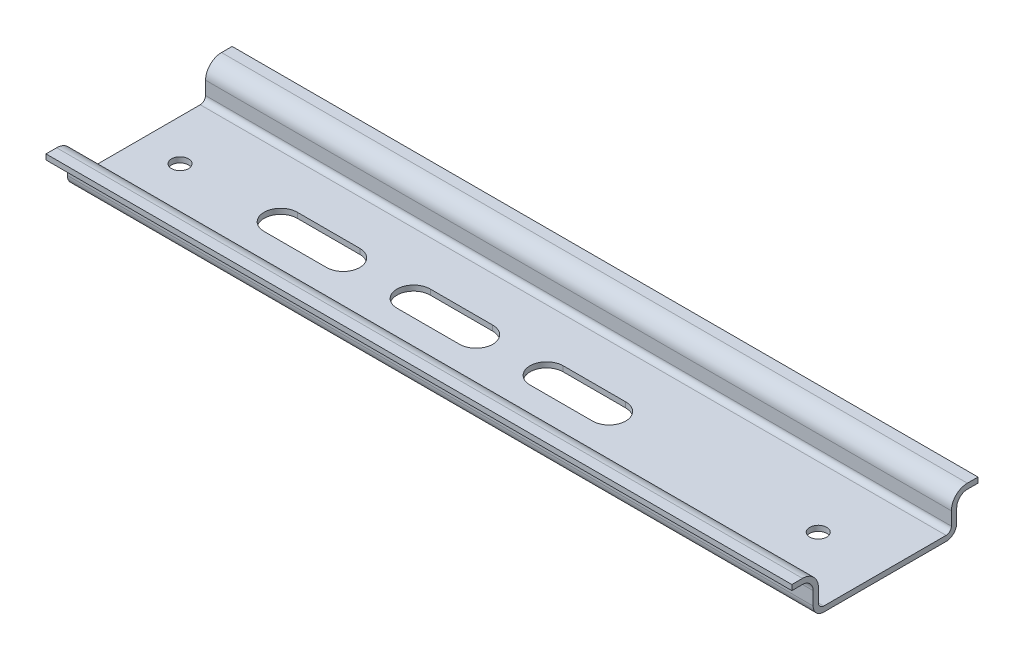
SolidWorks part; units mm, degrees
ref_plane "Front Plane" through (0, 0, 0) normal (0, 0, 1) x (1, 0, 0)
ref_plane "Top Plane" through (0, 0, 0) normal (0, 1, 0) x (1, 0, 0)
ref_plane "Right Plane" through (0, 0, 0) normal (1, 0, 0) x (0, 0, -1)
sketch "Sketch1" plane through (0, 0, 0) normal (1, 0, 0) x (0, 0, -1)
  line L0 (0, 0) -> (0, 18.2344) construction
  line L1 (0, 0) -> (26.621, 0) construction
  line L2 (-11.5, 0) -> (11.5, 0)
  line L3 (13.5, 2) -> (13.5, 4.5)
  line L4 (15.5, 6.5) -> (17.5, 6.5)
  line L5 (-13.5, 2) -> (-13.5, 4.5)
  line L6 (-15.5, 6.5) -> (-17.5, 6.5)
  arc A0 (13.5, 2) -> (11.5, 0) centre (11.5, 2) cw
  arc A1 (15.5, 6.5) -> (13.5, 4.5) centre (15.5, 4.5) ccw
  arc A2 (-13.5, 2) -> (-11.5, 0) centre (-11.5, 2) ccw
  arc A3 (-15.5, 6.5) -> (-13.5, 4.5) centre (-15.5, 4.5) cw
  point P9 (13.5, 0)
  dimension "D1" = 2
  dimension "D3" = 2
  dimension "D2" = 6.5
  dimension "D4" = 35
  dimension "D5" = 27
extrude "Extrude-Thin1" add sketch "Sketch1" along normal up to surface (82.739 mm away) and the other way blind 57.5 thin thin type one direction wall 1
sketch "Sketch2" plane through (0, 0, 0) normal (0, -1, 0) x (1, 0, 0)
  line L0 (0, 6.6969) -> (0, 0) construction
  line L1 (0, 0) -> (9.9599, 0) construction
  line L2 (-5.875, 3.125) -> (5.875, 3.125)
  line L3 (-5.875, -3.125) -> (5.875, -3.125)
  arc A0 (5.875, 3.125) -> (5.875, -3.125) centre (5.875, 0) cw
  arc A1 (-5.875, 3.125) -> (-5.875, -3.125) centre (-5.875, 0) ccw
  point P6 (0, 3.125)
  point P12 (0, -3.125)
  dimension "D2" = 11.75
  dimension "D1" = 6.25
extrude "Cut-Extrude1" cut sketch "Sketch2" against normal up to next
pattern_linear "LPattern1" count 2 spacing 25 along (1, 0, 0) count 2 spacing 25 along (-1, 0, 0) of "Cut-Extrude1"
sketch "Szkic1" plane through (0, 0, 0) normal (0, -1, 0) x (1, 0, 0)
  circle A0 centre (70.2, 0) radius 1.6
  circle A1 centre (-49.8, 0) radius 1.6
extrude "Wytnij-wyciągnięcie1" cut sketch "Szkic1" against normal through all
